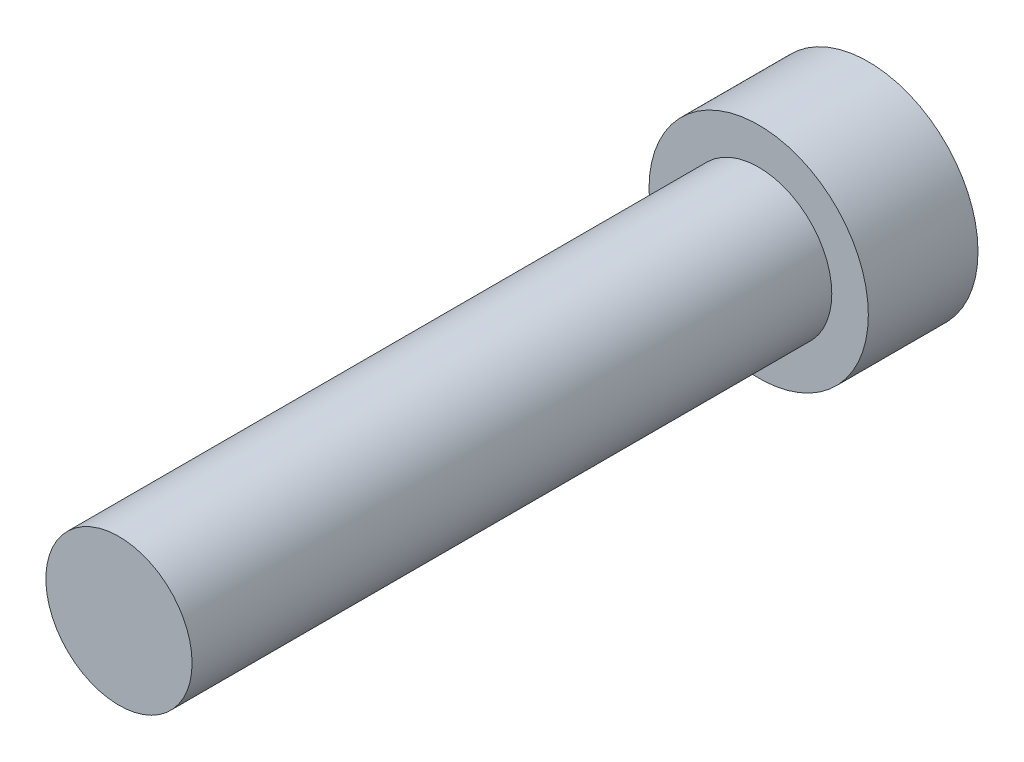
SolidWorks part; units mm, degrees
ref_plane "前视基准面" through (0, 0, 0) normal (0, 0, 1) x (1, 0, 0)
ref_plane "上视基准面" through (0, 0, 0) normal (0, 1, 0) x (1, 0, 0)
ref_plane "右视基准面" through (0, 0, 0) normal (1, 0, 0) x (0, 0, -1)
sketch "草图1" plane through (0, 0, 0) normal (0, 0, 1) x (1, 0, 0)
  line L1 (3.4641, 0) -> (1.7321, 3)
  line L2 (1.7321, 3) -> (-1.7321, 3)
  line L3 (-1.7321, 3) -> (-3.4641, 0)
  line L4 (-3.4641, 0) -> (-1.7321, -3)
  line L5 (-1.7321, -3) -> (1.7321, -3)
  line L6 (1.7321, -3) -> (3.4641, 0)
  circle A0 centre (0, 0) radius 6
  circle A1 centre (0, 0) radius 3 construction
  dimension "D1" = 12
  dimension "D2" = 6
extrude "凸台-拉伸1" add sketch "草图1" along normal blind 6
sketch "草图2" plane through (0, 0, 6) normal (0, 0, 1) x (1, 0, 0)
  circle A0 centre (0, 0) radius 4
  dimension "D1" = 8
extrude "凸台-拉伸2" add sketch "草图2" along normal blind 35
